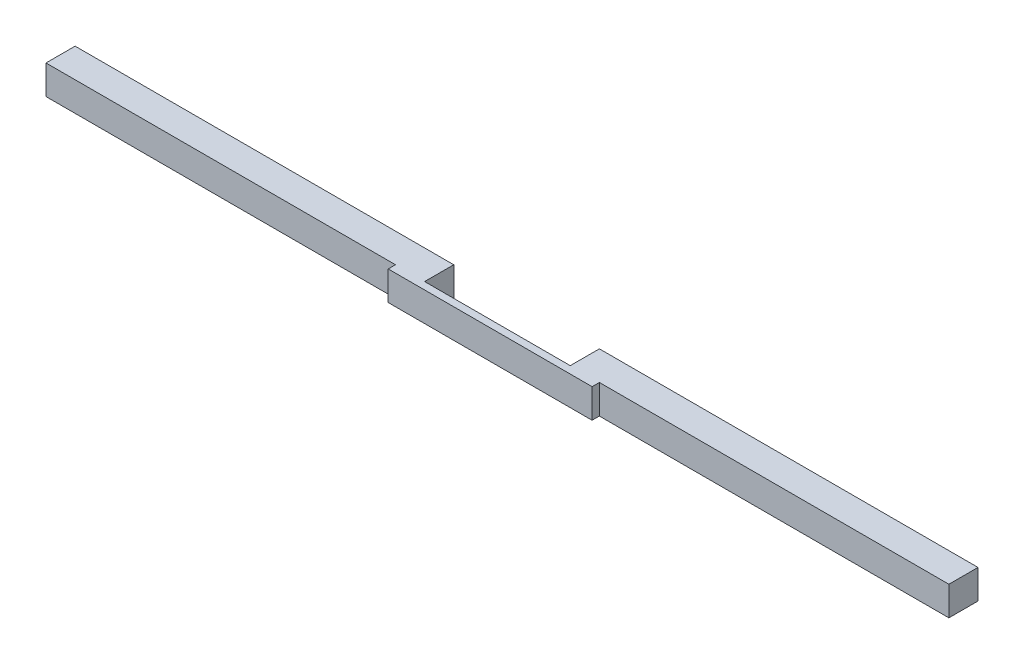
SolidWorks part; units mm, degrees
ref_plane "Front Plane" through (0, 0, 0) normal (0, 0, 1) x (1, 0, 0)
ref_plane "Top Plane" through (0, 0, 0) normal (0, 1, 0) x (1, 0, 0)
ref_plane "Right Plane" through (0, 0, 0) normal (1, 0, 0) x (0, 0, -1)
sketch "Sketch1" plane through (0, 0, 0) normal (0, 1, 0) x (1, 0, 0)
  line L0 (330.2, 0) -> (330.2, 25.4)
  line L1 (0, 0) -> (304.8, 0)
  line L2 (0, 0) -> (0, 25.4)
  line L3 (0, 25.4) -> (330.2, 25.4)
  line L4 (787.4, 0) -> (787.4, 25.4)
  line L5 (330.2, 0) -> (457.2, 0)
  line L6 (304.8, 0) -> (304.8, -6.35)
  line L7 (304.8, -6.35) -> (482.6, -6.35)
  line L8 (482.6, 0) -> (482.6, -6.35)
  line L9 (457.2, 0) -> (457.2, 25.4)
  line L10 (457.2, 25.4) -> (787.4, 25.4)
  line L11 (482.6, 0) -> (787.4, 0)
  dimension "D1" = 787.4
  dimension "D2" = 25.4
  dimension "D3" = 6.35
  dimension "D4" = 25.4
  dimension "D5" = 25.4
  dimension "D6" = 127
  dimension "D7" = 330.2
extrude "Boss-Extrude1" add sketch "Sketch1" along normal blind 25.4
